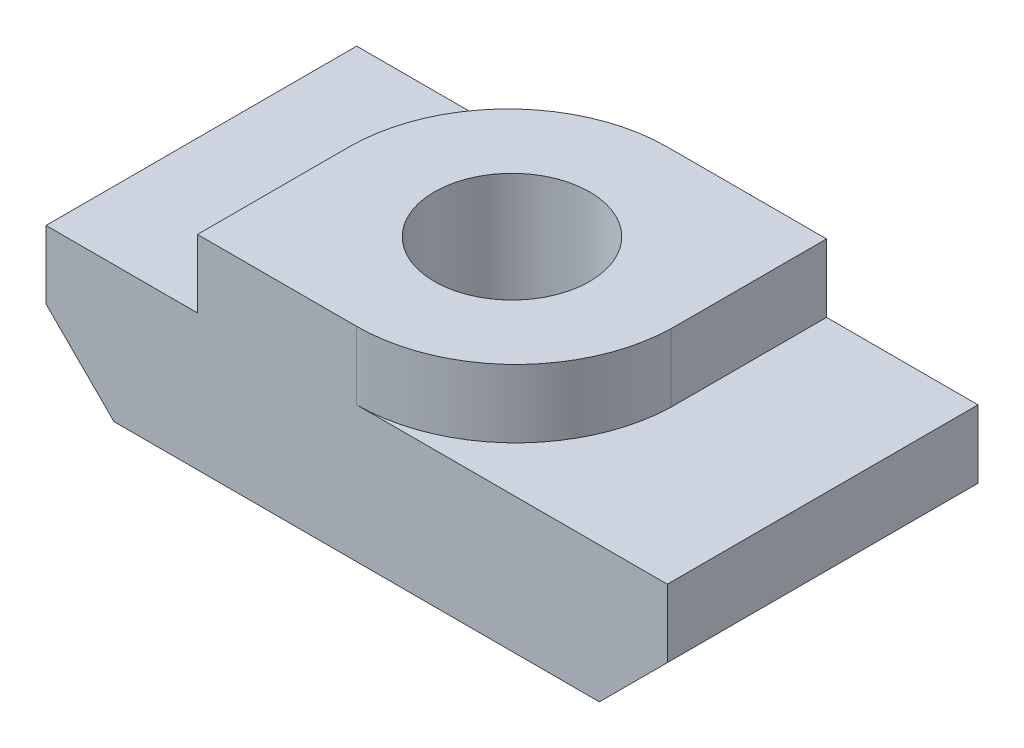
SolidWorks part; units mm, degrees
material "6061 Alloy"
ref_plane "Front Plane" through (0, 0, 0) normal (0, 0, 1) x (1, 0, 0)
ref_plane "Top Plane" through (0, 0, 0) normal (0, 1, 0) x (1, 0, 0)
ref_plane "Right Plane" through (0, 0, 0) normal (1, 0, 0) x (0, 0, -1)
sketch "Sketch1" plane through (0, 0, 0) normal (0, 0, 1) x (1, 0, 0)
  line L0 (0, 5.25) -> (0, 0)
  line L1 (0, -55) -> (0, 55) construction
  line L2 (0, 0) -> (6.25, 0)
  line L3 (55, 0) -> (-55, 0) construction
  line L4 (6.25, 0) -> (8, 1.75)
  line L5 (8, 1.75) -> (8, 3.5)
  line L6 (8, 3.5) -> (4.1, 3.5)
  line L7 (4.1, 3.5) -> (4.1, 5.25)
  line L8 (4.1, 5.25) -> (0, 5.25)
  dimension "D1" = 3.5
  dimension "D2" = 8
  dimension "D3" = 45
  dimension "D4" = 4.1
  dimension "D5" = 1.75
  dimension "D6" = 1.75
extrude "Boss-Extrude1" add sketch "Sketch1" along normal blind 8
mirror "Mirror1" about plane through (0, 0, 0) normal (1, 0, 0) of bodies 101
sketch "Sketch2" plane through (0, 5.25, 0) normal (0, 1, 0) x (1, 0, 0)
  line L0 (0, -2.8875) -> (0, 2.8875) construction
  line L1 (-2.8875, 0) -> (2.8875, 0) construction
  circle A0 centre (0, -4) radius 2
  dimension "D1" = 4
  dimension "D2" = 4
extrude "Cut-Extrude1" cut sketch "Sketch2" against normal blind 8 contours A0
sketch "Sketch3" plane through (0, 5.25, 0) normal (0, 1, 0) x (1, 0, 0)
  line L0 (4.1, -8) -> (-4.1, -8) construction
  line L2 (0, -2.8875) -> (0, 2.8875) construction
  line L3 (0, -8) -> (5.7282, -10.1248)
  line L4 (5.7282, -10.1248) -> (4.1, -4)
  line L5 (4.1, -8) -> (4.1, 0) construction
  line L6 (-2.8875, 0) -> (2.8875, 0) construction
  line L7 (-4.1, -4.1) -> (-7.6858, 1.6159)
  line L8 (-4.1, -8) -> (-4.1, 0) construction
  line L9 (-7.6858, 1.6159) -> (0, 0)
  arc A0 (0, -8) -> (4.1, -4) centre (0, -3.8988) ccw
  arc A1 (0, 0) -> (-4.1, -4.1) centre (0, -4.1) ccw
  line M6 (4.1, 0) -> (-4.1, 0)
  line M7 (-4.1, 0) -> (-4.1, -8)
  line M8 (-4.1, -8) -> (4.1, -8)
  line M9 (4.1, -8) -> (4.1, 0)
extrude "Cut-Extrude2" cut sketch "Sketch3" against normal blind 1.75 contours A0 M8 M9 | A1 M6 M7
